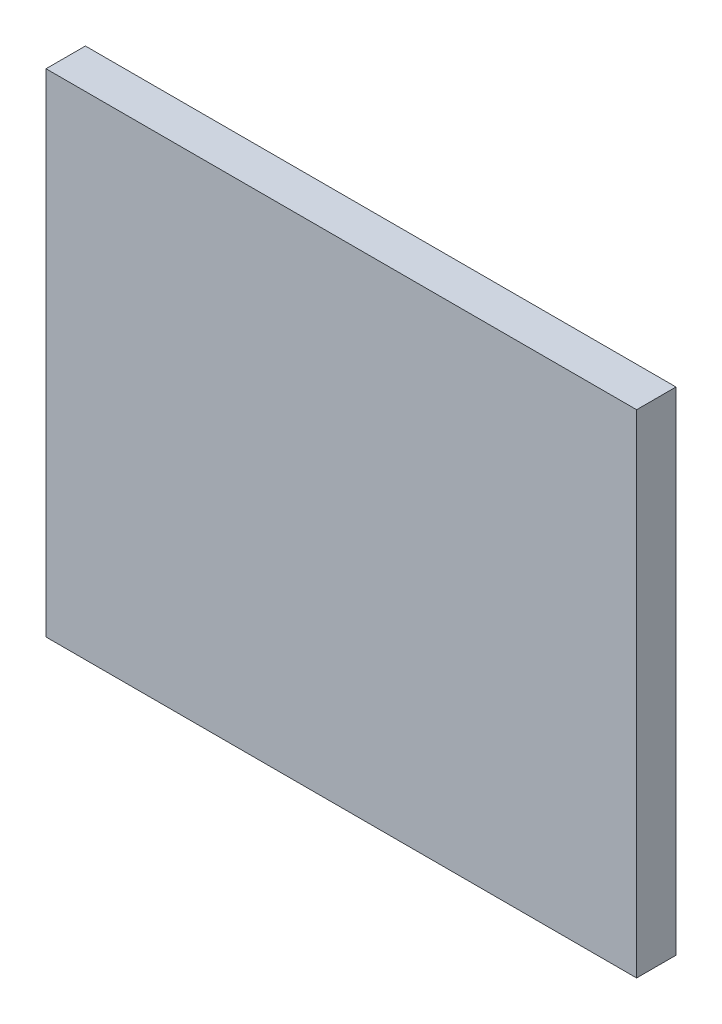
SolidWorks part; units mm, degrees
ref_plane "Front Plane" through (0, 0, 0) normal (0, 0, 1) x (1, 0, 0)
ref_plane "Top Plane" through (0, 0, 0) normal (0, 1, 0) x (1, 0, 0)
ref_plane "Right Plane" through (0, 0, 0) normal (1, 0, 0) x (0, 0, -1)
sketch "Sketch1" plane through (0, 0, 0) normal (0, 0, 1) x (1, 0, 0)
  line L1 (-150, -125) -> (150, -125)
  line L2 (-150, -125) -> (-150, 125)
  line L3 (-150, 125) -> (150, 125)
  line L4 (150, -125) -> (150, 125)
  line L5 (-150, -125) -> (150, 125) construction
  line L6 (-150, 125) -> (150, -125) construction
  point P0 (0, 0)
extrude "Boss-Extrude1" add sketch "Sketch1" along normal blind 20
